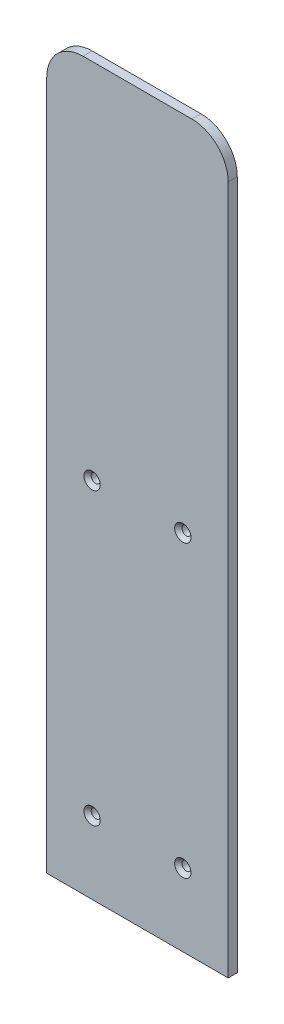
SolidWorks part; units mm, degrees
ref_plane "Front Plane" through (0, 0, 0) normal (0, 0, 1) x (1, 0, 0)
ref_plane "Top Plane" through (0, 0, 0) normal (0, 1, 0) x (1, 0, 0)
ref_plane "Right Plane" through (0, 0, 0) normal (1, 0, 0) x (0, 0, -1)
sketch "Sketch1" plane through (0, 0, 0) normal (0, 0, 1) x (1, 0, 0)
  line L1 (-31.75, 127) -> (31.75, 127)
  line L2 (-31.75, 127) -> (-31.75, -127)
  line L3 (-31.75, -127) -> (31.75, -127)
  line L4 (31.75, 127) -> (31.75, -127)
  line L5 (-31.75, 127) -> (31.75, -127) construction
  line L6 (-31.75, -127) -> (31.75, 127) construction
  point P0 (0, 0)
  dimension "D1" = 63.5
  dimension "D2" = 254
extrude "Boss-Extrude1" add sketch "Sketch1" along normal blind 3.175
sketch "Sketch2" plane through (0, 0, 3.175) normal (0, 0, 1) x (1, 0, 0)
  line L0 (-31.75, -127) -> (31.75, -127) construction
  line L1 (15.875, 0) -> (-15.875, 0) construction
  line L2 (15.875, 0) -> (15.875, -101.6) construction
  line L3 (15.875, -101.6) -> (-15.875, -101.6) construction
  line L4 (-15.875, 0) -> (-15.875, -101.6) construction
  circle A0 centre (15.875, -101.6) radius 1.5875
  circle A1 centre (-15.875, -101.6) radius 1.5875
  circle A2 centre (15.875, 0) radius 1.5875
  circle A3 centre (-15.875, 0) radius 1.5875
  dimension "D1" = 3.175
  dimension "D2" = 31.75
  dimension "D3" = 15.875
  dimension "D4" = 25.4
  dimension "D5" = 101.6
extrude "Cut-Extrude1" cut sketch "Sketch2" against normal up to next
chamfer "Chamfer1" distance 1.27 angle 45 4 edges at (-14.2875, -101.6, 3.175) (17.4625, -101.6, 3.175) (-14.2875, 0, 3.175) (17.4625, 0, 3.175)
fillet "Fillet1" radius 12.7 2 edges at (31.75, 127, 1.5875) (-31.75, 127, 1.5875)
